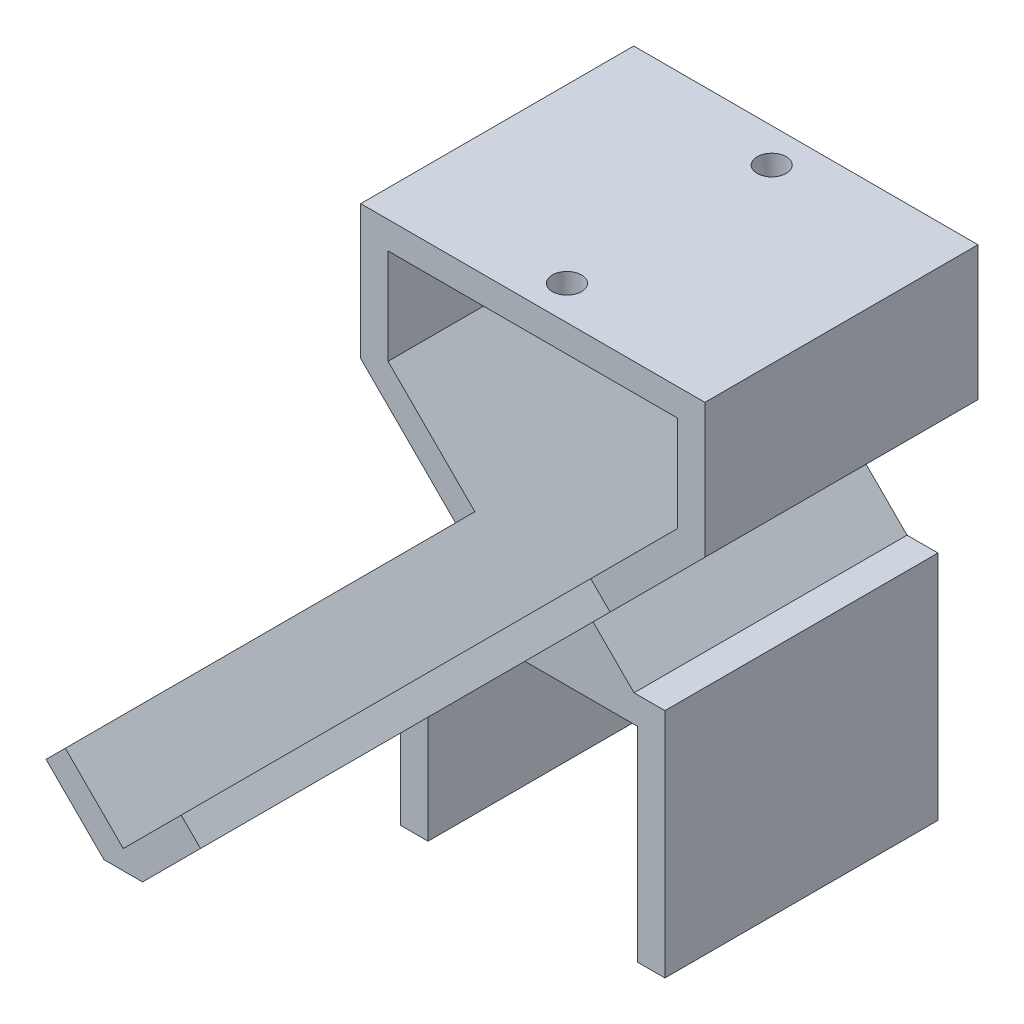
SolidWorks part; units mm, degrees
ref_plane "Front Plane" through (0, 0, 0) normal (0, 0, 1) x (1, 0, 0)
ref_plane "Top Plane" through (0, 0, 0) normal (0, 1, 0) x (1, 0, 0)
ref_plane "Right Plane" through (0, 0, 0) normal (1, 0, 0) x (0, 0, -1)
sketch "Sketch1" plane through (0, 0, 0) normal (0, 0, 1) x (1, 0, 0)
  line L0 (0, 0) -> (-13.4704, 13.4704)
  line L1 (-13.4704, 13.4704) -> (-13.4704, 22.3604)
  line L2 (13.4704, 13.4704) -> (0, 0)
  line L3 (-13.4704, 22.3604) -> (13.4704, 22.3604)
  line L4 (13.4704, 22.3604) -> (13.4704, 13.4704)
  line L5 (0, -3.5921) -> (-16.0104, 12.4183)
  line L6 (-16.0104, 12.4183) -> (-16.0104, 24.9004)
  line L7 (-16.0104, 24.9004) -> (16.0104, 24.9004)
  line L8 (16.0104, 24.9004) -> (16.0104, 12.4183)
  line L9 (16.0104, 12.4183) -> (0, -3.5921)
  dimension "D1" = 19.05
  dimension "D2" = 8.89
  dimension "D3" = 2.54
extrude "Boss-Extrude1" add sketch "Sketch1" along normal blind 25.4
sketch "Sketch2" plane through (0, 0, 25.4) normal (0, 0, 1) x (1, 0, 0)
  line L0 (0, 0) -> (-5.3882, 5.3882)
  line L1 (0, 0) -> (5.3882, 5.3882)
  line L2 (-7.1842, 3.5921) -> (-5.3882, 5.3882)
  line L3 (0, 0) -> (0, -3.5921) construction
  line L4 (7.1842, 3.5921) -> (5.3882, 5.3882)
  line L5 (0, -3.5921) -> (16.0104, 12.4183)
  line L6 (16.0104, 12.4183) -> (16.0104, 24.9004)
  line L7 (16.0104, 24.9004) -> (-16.0104, 24.9004)
  line L8 (-16.0104, 24.9004) -> (-16.0104, 12.4183)
  line L9 (-16.0104, 12.4183) -> (0, -3.5921)
  line L10 (0, -3.5921) -> (7.1842, 3.5921)
  line L14 (-7.1842, 3.5921) -> (0, -3.5921)
  dimension "D2" = 10.16
  dimension "D1" = 0
extrude "Boss-Extrude2" add sketch "Sketch2" along normal blind 38.1
hole_wizard "#6-32 Tapped Hole1" positions "Sketch4" profile "Sketch3" tap size "#6-32" standard "ANSI Inch"
sketch "Sketch4" plane through (0, 24.9004, 0) normal (0, 1, 0) x (1, 0, 0)
  line L0 (0, -25.4) -> (0, 0) construction
  line L1 (16.0104, -25.4) -> (-16.0104, -25.4) construction
  line L2 (16.0104, 0) -> (-16.0104, 0) construction
  line L4 (-16.0104, -12.7) -> (16.0104, -12.7) construction
  line L5 (-16.0104, -25.4) -> (-16.0104, 0) construction
  line L6 (16.0104, -25.4) -> (16.0104, 0) construction
  point P15 (0, -3.175)
  point P17 (0, -22.225)
  dimension "D1" = 19.05
sketch "Sketch3" plane through (0, 24.9004, 3.175) normal (1, 0, 0) x (0, 0, 1)
  line L0 (0, 0) -> (0, 13.5127)
  line L1 (0, 13.5127) -> (1.3525, 12.7)
  line L2 (1.3525, 12.7) -> (1.3525, 0)
  line L5 (1.3525, 0) -> (0, 0)
  line L10 (0, 13.5127) -> (-1.3525, 12.7) construction
  line L11 (0, -6.35) -> (0, 107.95) construction
  dimension "Tap Drill Dia." = 2.7051
  dimension "Tap Drill Depth" = 12.7
  dimension "Drill Angle" = 118
cosmetic thread "Hole Thread1" parameters "D1"=2.54, "D2"=3.5052
cosmetic thread "Hole Thread2" parameters "D1"=2.54, "D2"=3.5052
chamfer "Chamfer1" distance 2.54 angle 45 1 edges at (0, -3.5921, 31.75)
sketch "Sketch5" plane through (0, 0, 0) normal (0, 0, -1) x (-1, 0, 0)
  line L0 (0, -1.7961) -> (0, -18.4246) construction
  line L1 (-1.7961, -1.7961) -> (1.7961, -1.7961) construction
  line L2 (1.7961, -1.7961) -> (-1.7961, -1.7961)
  line L3 (-1.7961, -1.7961) -> (-12.29, -1.7961)
  line L4 (-12.29, -1.7961) -> (-12.29, -23.3361)
  line L5 (-12.29, -23.3361) -> (-9.75, -23.3361)
  line L6 (-9.75, -23.3361) -> (-9.75, -4.3361)
  line L7 (-9.75, -4.3361) -> (9.75, -4.3361)
  line L8 (9.75, -23.3361) -> (9.75, -4.3361)
  line L9 (12.29, -23.3361) -> (9.75, -23.3361)
  line L10 (12.29, -1.7961) -> (12.29, -23.3361)
  line L11 (1.7961, -1.7961) -> (12.29, -1.7961)
  point P15 (0, -4.3361)
  dimension "D1" = 2.54
  dimension "D2" = 2.54
  dimension "D3" = 19
  dimension "D4" = 19.5
extrude "Boss-Extrude3" add sketch "Sketch5" against normal blind 25.4
chamfer "Chamfer2" distance 7.62 angle 45 2 edges
